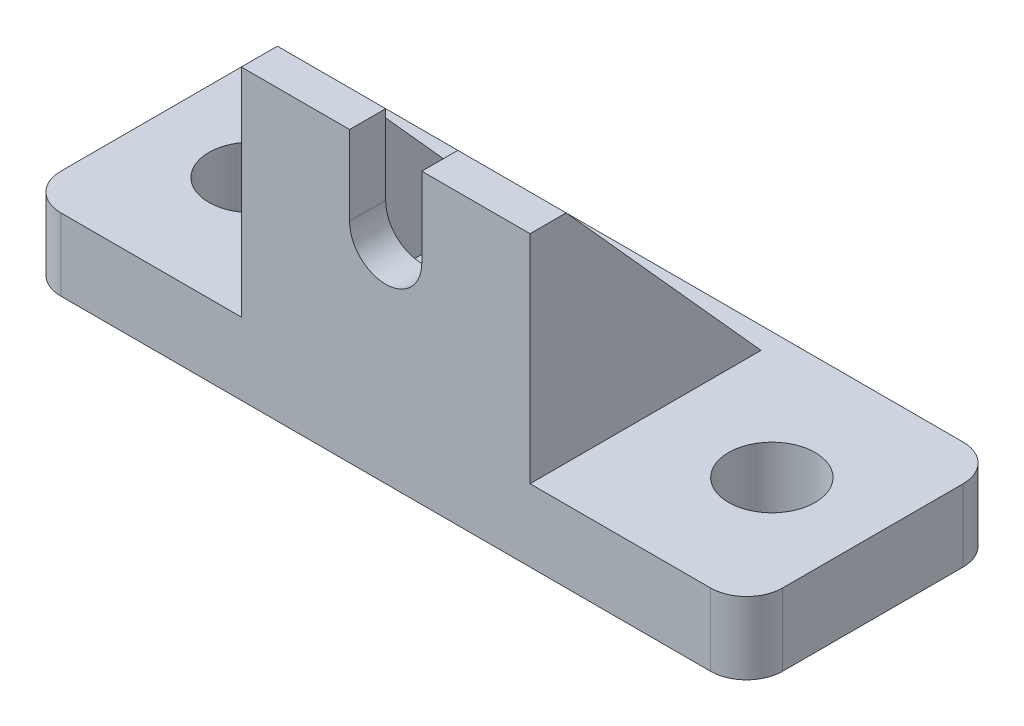
SolidWorks part; units mm, degrees
ref_plane "Ön Düzlem" through (0, 0, 0) normal (0, 0, 1) x (1, 0, 0)
ref_plane "Üst Düzlem" through (0, 0, 0) normal (0, 1, 0) x (1, 0, 0)
ref_plane "Sağ Düzlem" through (0, 0, 0) normal (1, 0, 0) x (0, 0, -1)
sketch "Çizim1" plane through (0, 0, 0) normal (0, 1, 0) x (1, 0, 0)
  line L2 (-142.6762, -27.0166) -> (-52.6762, -27.0166)
  line L3 (-147.6762, -32.0166) -> (-147.6762, -57.0166)
  line L4 (-142.6762, -62.0166) -> (-52.6762, -62.0166)
  line L5 (-47.6762, -32.0166) -> (-47.6762, -57.0166)
  arc A0 (-147.6762, -57.0166) -> (-142.6762, -62.0166) centre (-142.6762, -57.0166) ccw
  arc A1 (-52.6762, -62.0166) -> (-47.6762, -57.0166) centre (-52.6762, -57.0166) ccw
  arc A2 (-52.6762, -27.0166) -> (-47.6762, -32.0166) centre (-52.6762, -32.0166) cw
  arc A3 (-142.6762, -27.0166) -> (-147.6762, -32.0166) centre (-142.6762, -32.0166) ccw
  circle A4 centre (-133.6762, -44.5166) radius 6
  circle A6 centre (-61.6762, -44.5166) radius 6
  dimension "D1" = 5
  dimension "D4" = 12
  dimension "D5" = 12
  dimension "D7" = 14
  dimension "D8" = 14
  dimension "D2" = 17.5
  dimension "D3" = 35
  dimension "D6" = 17.5
  dimension "D9" = 100
extrude "Yükseklik-Ekstrüzyon1" add sketch "Çizim1" along normal blind 10
ref_plane "Düzlem1" through (-117.6762, 0, 0) normal (-1, 0, 0) x (0, 0, 1)
ref_plane "Düzlem2" through (-77.6762, 0, 0) normal (1, 0, 0) x (0, 0, -1)
sketch "Çizim3" plane through (0, 0, 62.0166) normal (0, 0, 1) x (1, 0, 0)
  line L0 (-117.6762, 5.5) -> (-117.6762, -5.5) construction
  line L1 (-117.6762, 10) -> (-77.6762, 10)
  line L2 (-117.6762, 10) -> (-117.6762, 40)
  line L3 (-117.6762, 40) -> (-77.6762, 40)
  line L4 (-77.6762, 10) -> (-77.6762, 40)
  line L5 (-142.6762, 10) -> (-52.6762, 10) construction
  line L6 (-77.6762, -5.5) -> (-77.6762, 5.5) construction
  line L8 (-102.6762, 40) -> (-92.6762, 40)
  line L9 (-102.6762, 40) -> (-102.6762, 29)
  line L11 (-92.6762, 40) -> (-92.6762, 29)
  arc A0 (-102.6762, 29) -> (-92.6762, 29) centre (-97.6762, 28.9367) ccw
  line M11 (-52.6762, 10) -> (-142.6762, 10)
  dimension "D5" = 5.0004
  dimension "D1" = 30
  dimension "D2" = 15
  dimension "D3" = 15
  dimension "D4" = 11
extrude "Yükseklik-Ekstrüzyon2" add sketch "Çizim3" against normal blind 5 contours A0 L9 L3 L2 L4 L11 M11
sketch "Çizim5" plane through (-77.6762, 0, 0) normal (1, 0, 0) x (0, 0, -1)
  line L0 (-57.0166, 40) -> (-30.0166, 10)
  line L1 (-27.0166, 10) -> (-32.0166, 10) construction
  dimension "D1" = 3
rib "Feder1" sketch "Çizim5" sketch "Çizim5" thickness 5 extrusion direction parallel to sketch draft on no parameters "D1"=5
sketch "Çizim6" plane through (-117.6762, 0, 0) normal (-1, 0, 0) x (0, 0, 1)
  line L0 (57.0166, 40) -> (30.0166, 10)
rib "Feder8" sketch "Çizim6" sketch "Çizim6" thickness 5 extrusion direction parallel to sketch draft on no parameters "D1"=5
